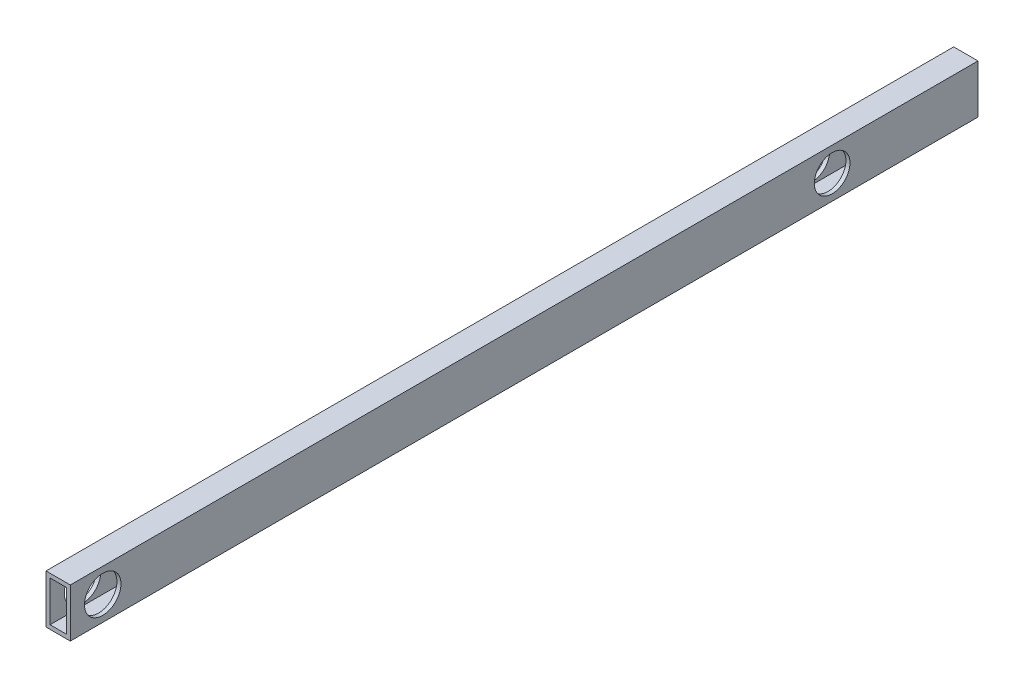
SolidWorks part; units mm, degrees
ref_plane "Front Plane" through (0, 0, 0) normal (0, 0, 1) x (1, 0, 0)
ref_plane "Top Plane" through (0, 0, 0) normal (0, 1, 0) x (1, 0, 0)
ref_plane "Right Plane" through (0, 0, 0) normal (1, 0, 0) x (0, 0, -1)
sketch "Sketch1" plane through (0, 0, 0) normal (0, 0, 1) x (1, 0, 0)
  line L1 (0, 0) -> (19.05, 0)
  line L2 (0, 0) -> (0, 38.1)
  line L3 (0, 38.1) -> (19.05, 38.1)
  line L4 (19.05, 0) -> (19.05, 38.1)
  dimension "D1" = 19.05
  dimension "D2" = 38.1
extrude "Extrude-Thin1" add sketch "Sketch1" along normal blind 711.2 thin thin type one direction reverse wall 3.175
sketch "Sketch3" plane through (19.05, 0, 0) normal (1, 0, 0) x (0, 0, -1)
  line L0 (-711.2, 38.1) -> (0, 38.1) construction
  line L1 (0, 0) -> (0, 38.1) construction
  circle A0 centre (-114.3, 19.05) radius 13.97
  point P4 (0, 19.05)
  dimension "D1" = 19.05
  dimension "D2" = 114.3
extrude "Cut-Extrude2" cut sketch "Sketch3" against normal through all
sketch "Sketch4" plane through (19.05, 0, 0) normal (1, 0, 0) x (0, 0, -1)
  line L0 (-711.2, 38.1) -> (0, 38.1) construction
  line L1 (-711.2, 0) -> (-711.2, 38.1) construction
  circle A0 centre (-685.8, 19.05) radius 14.2875
  point P2 (0, 0)
  dimension "D1" = 19.05
  dimension "D2" = 28.575
  dimension "D3" = 25.4
extrude "Cut-Extrude3" cut sketch "Sketch4" against normal through all
